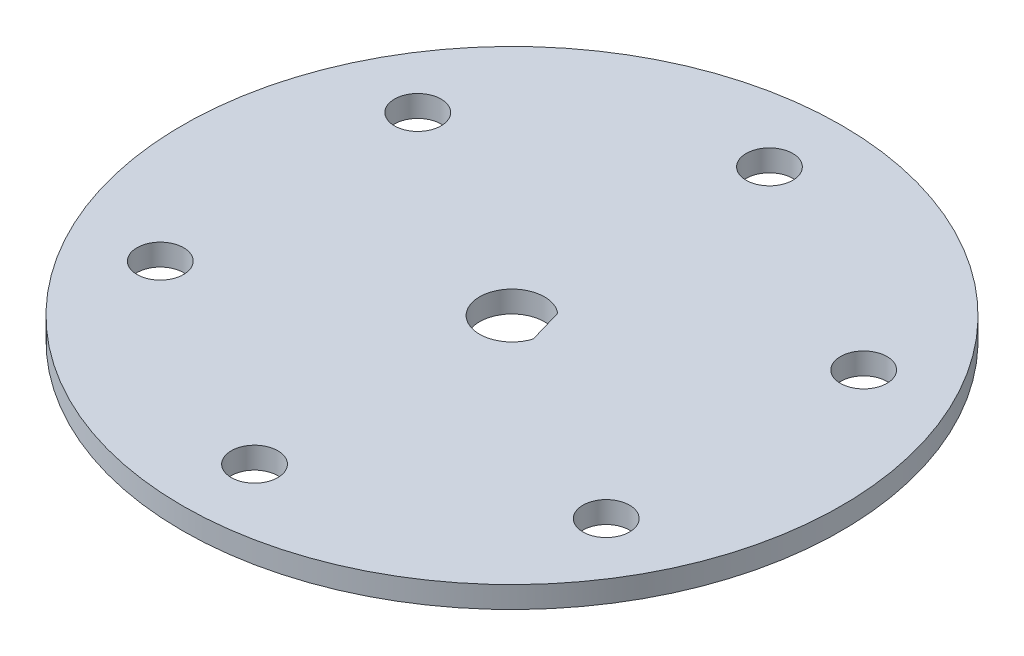
SolidWorks part; units mm, degrees
ref_plane "Front" through (0, 0, 0) normal (0, 0, 1) x (1, 0, 0)
ref_plane "Top" through (0, 0, 0) normal (0, 1, 0) x (1, 0, 0)
ref_plane "Right" through (0, 0, 0) normal (1, 0, 0) x (0, 0, -1)
sketch "Sketch1" plane through (0, 0, 0) normal (0, 1, 0) x (1, 0, 0)
  circle A1 centre (0, 0) radius 30.48
  circle A2 centre (0, -23.8125) radius 2.1526
  circle A3 centre (20.6222, -11.9062) radius 2.1526
  circle A4 centre (20.6222, 11.9063) radius 2.1526
  circle A5 centre (0, 23.8125) radius 2.1526
  circle A6 centre (-20.6222, 11.9062) radius 2.1527
  circle A7 centre (-20.6222, -11.9062) radius 2.1527
extrude "Boss-Extrude1" add sketch "Sketch1" along normal blind 2
sketch "Sketch2" plane through (0, 2, 0) normal (0, 1, 0) x (1, 0, 0)
  line L0 (2.8645, -0.8913) -> (1.932, 2.295)
  circle A0 centre (0, 0) radius 3
  dimension "D1" = 3.32
extrude "Cut-Extrude1" cut sketch "Sketch2" against normal blind 10 contours L0 A0
